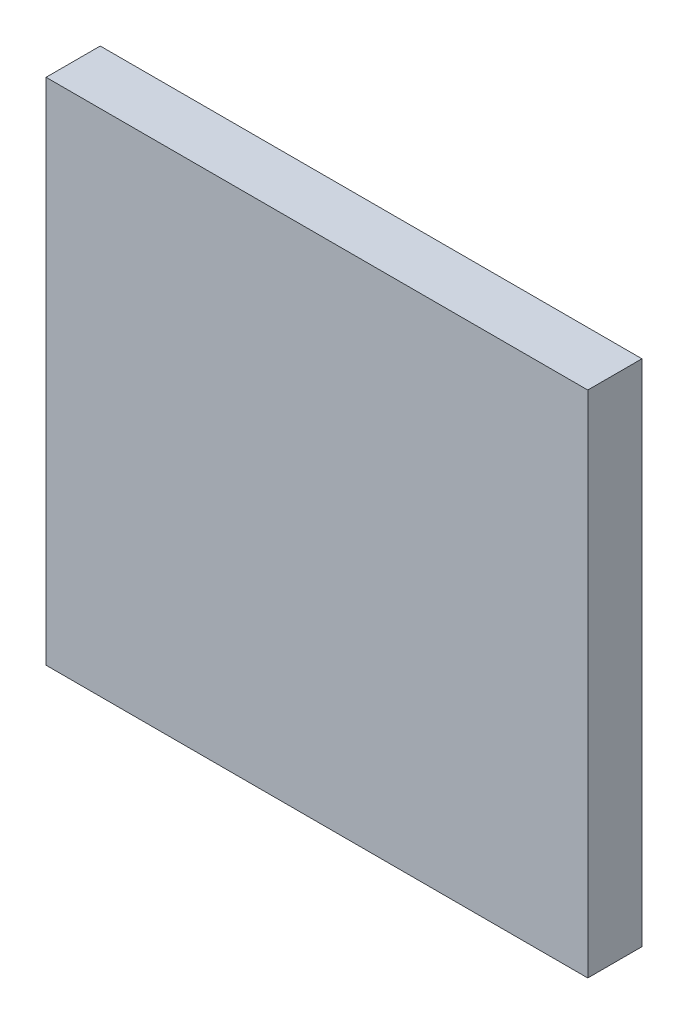
SolidWorks part; units mm, degrees
ref_plane "Front Plane" through (0, 0, 0) normal (0, 0, 1) x (1, 0, 0)
ref_plane "Top Plane" through (0, 0, 0) normal (0, 1, 0) x (1, 0, 0)
ref_plane "Right Plane" through (0, 0, 0) normal (1, 0, 0) x (0, 0, -1)
sketch "Sketch1" plane through (0, 0, 0) normal (0, 0, 1) x (1, 0, 0)
  line L1 (-50, -47) -> (50, -47)
  line L2 (-50, -47) -> (-50, 47)
  line L3 (-50, 47) -> (50, 47)
  line L4 (50, -47) -> (50, 47)
  line L5 (-50, -47) -> (50, 47) construction
  line L6 (-50, 47) -> (50, -47) construction
  point P0 (0, 0)
  dimension "D1" = 94
  dimension "D2" = 100
extrude "Boss-Extrude1" add sketch "Sketch1" along normal blind 10
